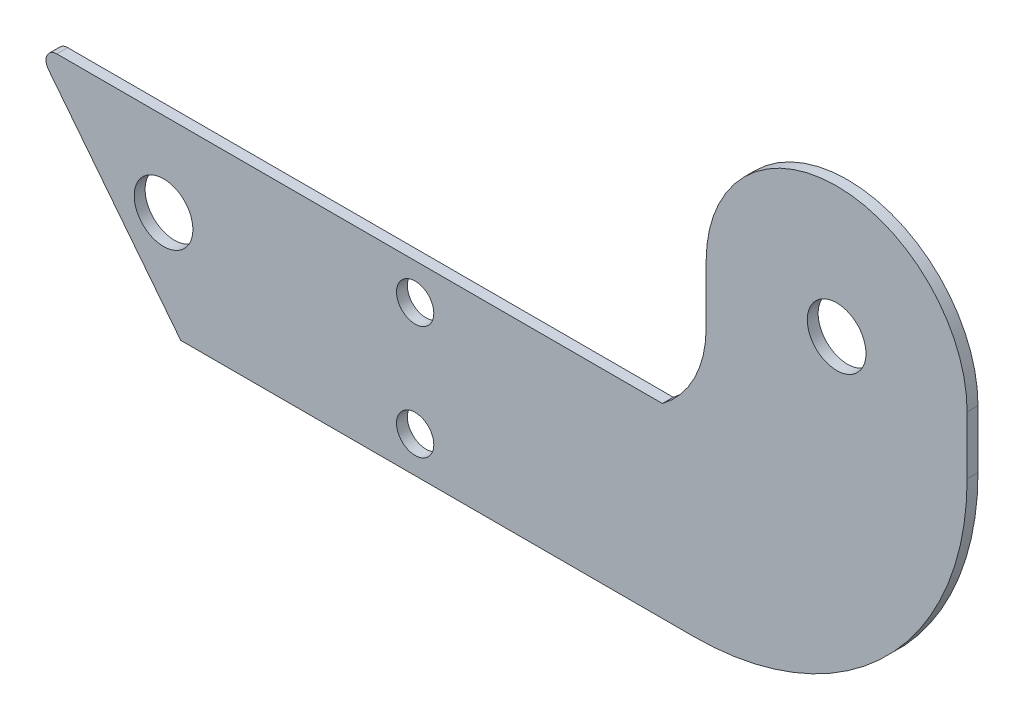
SolidWorks part; units mm, degrees
ref_plane "Plano frontal" through (0, 0, 0) normal (0, 0, 1) x (1, 0, 0)
ref_plane "Plano superior" through (0, 0, 0) normal (0, 1, 0) x (1, 0, 0)
ref_plane "Plano direito" through (0, 0, 0) normal (1, 0, 0) x (0, 0, -1)
sketch "Esboço1" plane through (0, 0, 0) normal (0, 0, 1) x (1, 0, 0)
  line L1 (-18.0186, 0) -> (-18.0186, -8)
  line L2 (-24.0556, -20.0277) -> (-110.7514, -20.0277)
  line L3 (-19.7146, -45.7332) -> (-90.5636, -45.7332)
  line L5 (-110.7514, -20.0277) -> (-90.5636, -45.7332)
  line L6 (18.0186, 0) -> (18.0186, -8)
  arc A0 (18.0186, 0) -> (-18.0186, 0) centre (0, 0) ccw
  arc A2 (-18.0186, -8) -> (-24.0556, -20.0277) centre (-33.0186, -8) cw
  circle A3 centre (0, 0) radius 4.05
  circle A4 centre (-58.1953, -25.0277) radius 2.5741
  circle A5 centre (-58.1953, -40.7332) radius 2.5741
  circle A6 centre (-92.935, -31.6398) radius 4.05
  arc A7 (18.0186, -8) -> (-19.7146, -45.7332) centre (-19.7146, -8) cw
  dimension "D1" = 5
  dimension "D2" = 5
  dimension "D3" = 6.8397
extrude "Ressalto-extrusão1" add sketch "Esboço1" along normal blind 1.5
fillet "Filete1" radius 1.5 1 edges at (-110.7514, -20.0277, 0.75)
